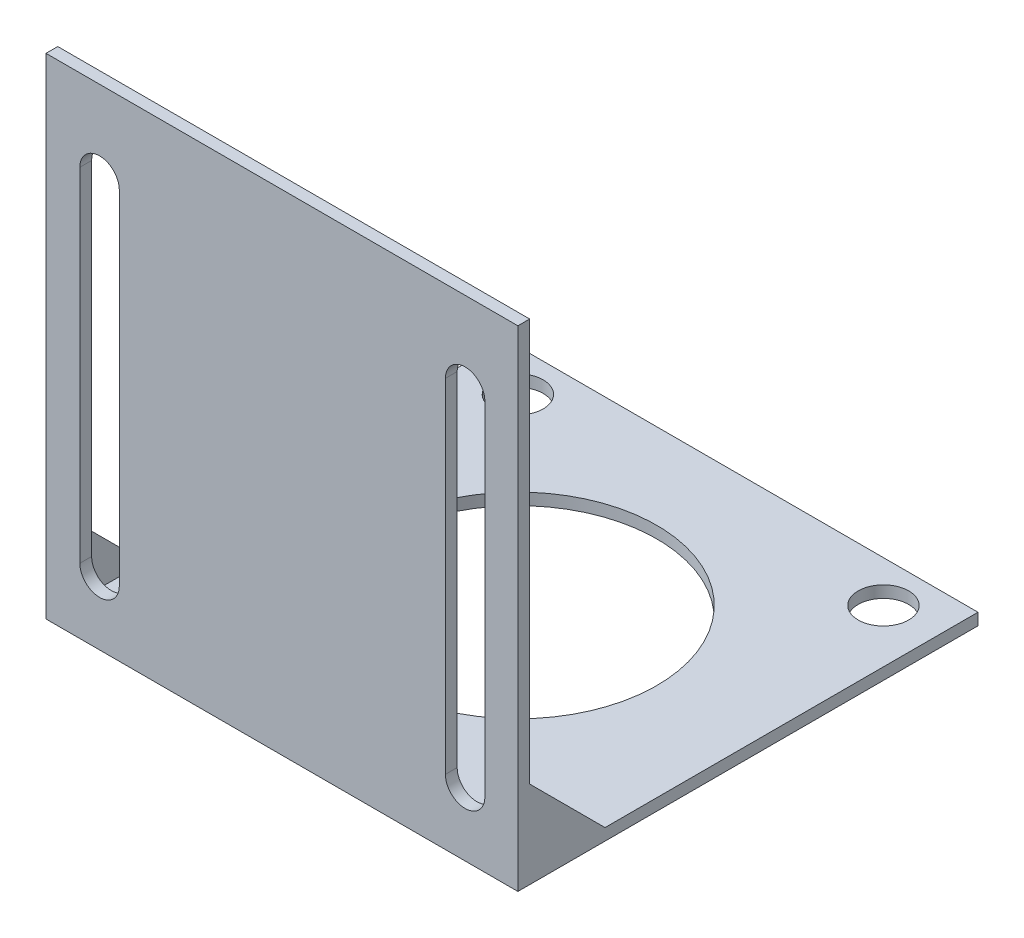
SolidWorks part; units mm, degrees
material "1060 Alloy"
ref_plane "Front Plane" through (0, 0, 0) normal (0, 0, 1) x (1, 0, 0)
ref_plane "Top Plane" through (0, 0, 0) normal (0, 1, 0) x (1, 0, 0)
ref_plane "Right Plane" through (0, 0, 0) normal (1, 0, 0) x (0, 0, -1)
sketch "Sketch1" plane through (0, 0, 0) normal (0, 1, 0) x (1, 0, 0)
  line L0 (15.109, 0) -> (15.109, -36.3752) construction
  line L1 (0, 0) -> (30.218, 0)
  line L2 (0, 0) -> (0, -30.218)
  line L3 (0, -30.218) -> (30.218, -30.218)
  line L4 (30.218, 0) -> (30.218, -30.218)
  line L5 (0, -15.109) -> (50.2878, -15.109) construction
  circle A0 centre (15.109, -15.109) radius 9.3599
  circle A1 centre (2.79, -2.79) radius 1.7018
  circle A2 centre (27.428, -2.79) radius 1.7018
  circle A3 centre (27.428, -27.428) radius 1.7018
  circle A4 centre (2.79, -27.428) radius 1.7018
  dimension "D1" = 24.638
  dimension "D2" = 24.638
  dimension "D3" = 3.4036
  dimension "D4" = 18.7198
  dimension "D5" = 2.79
extrude "Boss-Extrude1" add sketch "Sketch1" along normal blind 0.7937
sketch "Sketch2" plane through (0, 0, 30.218) normal (0, 0, 1) x (1, 0, 0)
  line L1 (0, 0) -> (30.218, 0)
  line L2 (0, 0) -> (0, 33.02)
  line L3 (0, 33.02) -> (30.218, 33.02)
  line L4 (30.218, 0) -> (30.218, 33.02)
  dimension "D1" = 33.02
extrude "Boss-Extrude2" add sketch "Sketch2" along normal blind 0.7937
sketch "Sketch3" plane through (30.218, 0, 0) normal (1, 0, 0) x (0, 0, -1)
  line L0 (-25.138, 0.7938) -> (-30.218, 5.8738)
  line L6 (-31.0118, 0) -> (0, 0)
  line L7 (0, 0) -> (0, 0.7937)
  line L8 (0, 0.7937) -> (-30.218, 0.7937)
  line L9 (-30.218, 0.7937) -> (-30.218, 33.02)
  line L10 (-30.218, 33.02) -> (-31.0118, 33.02)
  line L11 (-31.0118, 33.02) -> (-31.0118, 0)
  line L12 (-31.0118, 0) -> (0, 0)
  line L13 (0, 0) -> (0, 0.7937)
  line L14 (0, 0.7937) -> (-25.138, 0.7938)
  line L15 (-30.218, 5.8738) -> (-30.218, 33.02)
  line L16 (-30.218, 33.02) -> (-31.0118, 33.02)
  line L17 (-31.0118, 33.02) -> (-31.0118, 0)
  dimension "D2" = 135
  dimension "D3" = 5.08
  dimension "D1" = 0
extrude "Boss-Extrude3" add sketch "Sketch3" along normal blind 0.7937
sketch "Sketch4" plane through (0, 0, 0) normal (-1, 0, 0) x (0, 0, 1)
  line L0 (25.138, 0.7937) -> (30.218, 5.8738)
  line L6 (0, 0) -> (31.0118, 0)
  line L7 (31.0118, 0) -> (31.0118, 33.02)
  line L8 (31.0118, 33.02) -> (30.218, 33.02)
  line L9 (30.218, 33.02) -> (30.218, 0.7937)
  line L10 (30.218, 0.7937) -> (0, 0.7937)
  line L11 (0, 0.7937) -> (0, 0)
  line L12 (0, 0) -> (31.0118, 0)
  line L13 (31.0118, 0) -> (31.0118, 33.02)
  line L14 (31.0118, 33.02) -> (30.218, 33.02)
  line L15 (30.218, 33.02) -> (30.218, 5.8738)
  line L16 (25.138, 0.7937) -> (0, 0.7937)
  line L17 (0, 0.7937) -> (0, 0)
  dimension "D2" = 135
  dimension "D3" = 5.08
  dimension "D1" = 0
extrude "Boss-Extrude4" add sketch "Sketch4" along normal blind 0.7937
sketch "Sketch5" plane through (0, 0, 30.218) normal (0, 0, -1) x (-1, 0, 0)
  line L0 (-2.8178, 4.3955) -> (-2.8178, 27.5098) construction
  line L1 (-4.1473, 4.3955) -> (-4.1473, 27.5098)
  line L2 (-1.4883, 4.3955) -> (-1.4883, 27.5098)
  line L3 (-27.4558, 4.3955) -> (-27.4558, 27.5098) construction
  line L4 (-28.7853, 4.3955) -> (-28.7853, 27.5098)
  line L5 (-26.1263, 4.3955) -> (-26.1263, 27.5098)
  line L6 (-31.0118, 5.8738) -> (-31.0118, 33.02) construction
  arc A0 (-4.1473, 4.3955) -> (-1.4883, 4.3955) centre (-2.8178, 4.3955) ccw
  arc A1 (-1.4883, 27.5098) -> (-4.1473, 27.5098) centre (-2.8178, 27.5098) ccw
  arc A2 (-28.7853, 4.3955) -> (-26.1263, 4.3955) centre (-27.4558, 4.3955) ccw
  arc A3 (-26.1263, 27.5098) -> (-28.7853, 27.5098) centre (-27.4558, 27.5098) ccw
  point P2 (-2.8178, 15.9527)
  point P9 (-27.4558, 15.9527)
  point P16 (-26.1263, 27.5098)
  dimension "D1" = 24.638
  dimension "D2" = 3.556
extrude "Cut-Extrude1" cut sketch "Sketch5" against normal through all
